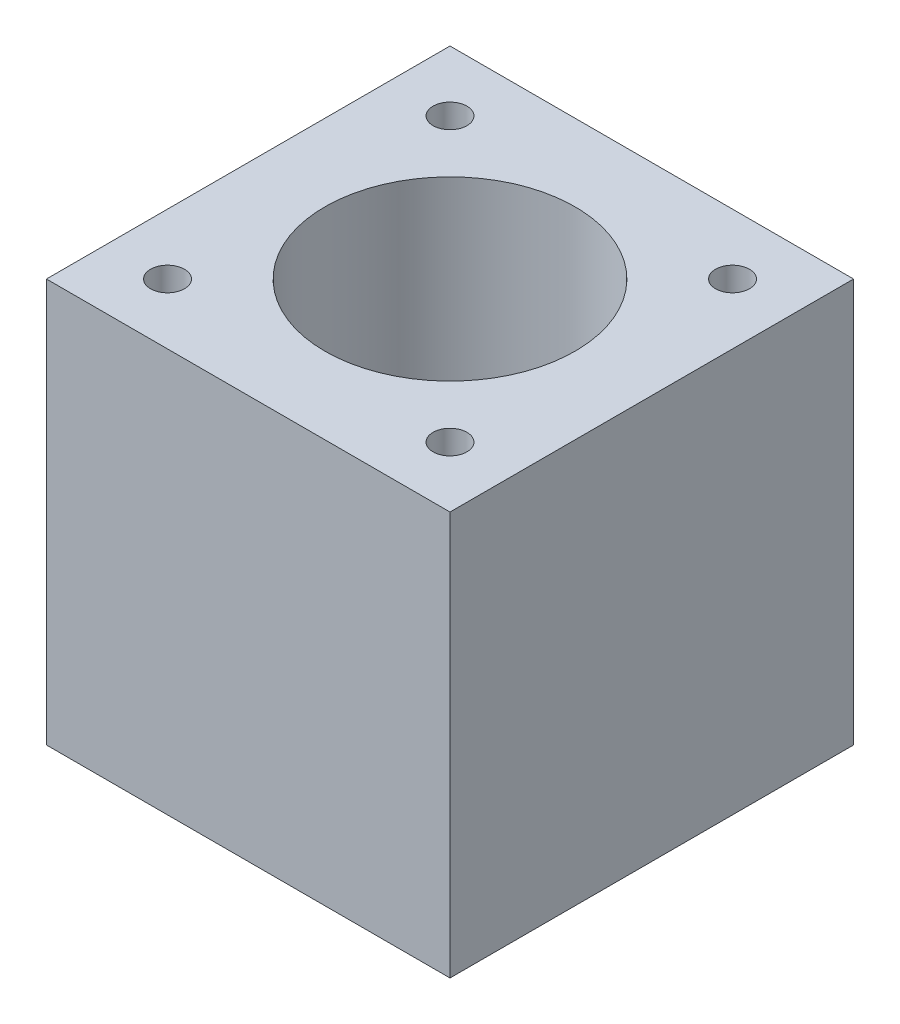
SolidWorks part; units mm, degrees
ref_plane "Front Plane" through (0, 0, 0) normal (0, 0, 1) x (1, 0, 0)
ref_plane "Top Plane" through (0, 0, 0) normal (0, 1, 0) x (1, 0, 0)
ref_plane "Right Plane" through (0, 0, 0) normal (1, 0, 0) x (0, 0, -1)
sketch "Sketch2" plane through (0, 0, 0) normal (0, 0, 1) x (1, 0, 0)
  line L1 (0, 0) -> (50, 0)
  line L2 (0, 0) -> (0, 50)
  line L3 (0, 50) -> (50, 50)
  line L4 (50, 0) -> (50, 50)
  dimension "D1" = 50
  dimension "D2" = 50
extrude "Boss-Extrude1" add sketch "Sketch2" along normal blind 50
sketch "Sketch5" plane through (0, 50, 0) normal (0, 1, 0) x (1, 0, 0)
  line L0 (-4.5853, -7.5) -> (61.8357, -7.5) construction
  line L1 (50, 0) -> (0, 0) construction
  line L2 (7.5, -13.925) -> (7.5, -52.7691) construction
  line L4 (0, -50) -> (0, 0) construction
  line L5 (-9.5178, -42.5) -> (63.0754, -42.5) construction
  line L6 (50, -50) -> (0, -50) construction
  line L7 (42.5, -63.4382) -> (42.5, -29.0794) construction
  line L8 (50, -50) -> (50, 0) construction
  circle A0 centre (7.5, -7.5) radius 2.1
  circle A1 centre (42.5, -7.5) radius 2.1
  circle A3 centre (7.5, -42.5) radius 2.1
  circle A4 centre (42.5, -42.5) radius 2.1
  dimension "D1" = 4.2
  dimension "D2" = 4.2
  dimension "D4" = 7.5
  dimension "D7" = 4.2
  dimension "D8" = 4.2
  dimension "D3" = 7.5
  dimension "D5" = 7.5
  dimension "D6" = 7.5
extrude "Cut-Extrude2" cut sketch "Sketch5" against normal up to next
cosmetic thread "Cosmetic Thread2" parameters "D2"=5
cosmetic thread "Cosmetic Thread3" parameters "D2"=5
cosmetic thread "Cosmetic Thread4" parameters "D2"=5
cosmetic thread "Cosmetic Thread5" parameters "D2"=5
sketch "Sketch6" plane through (0, 50, 0) normal (0, 1, 0) x (-1, 0, 0)
  line L0 (-50, 50) -> (0, 50) construction
  line L1 (0, 50) -> (0, 0) construction
  circle A0 centre (-25, 25) radius 15.5
  dimension "D3" = 31
  dimension "D1" = 25
  dimension "D2" = 25
extrude "Cut-Extrude3" cut sketch "Sketch6" against normal up to next contours A0
